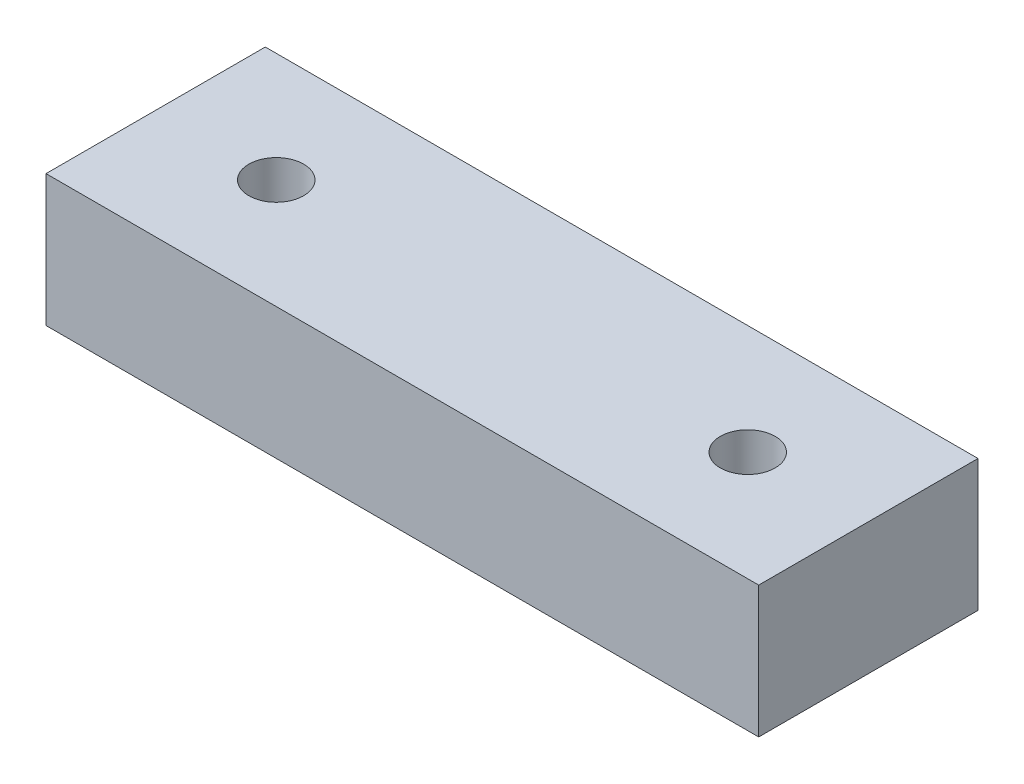
SolidWorks part; units mm, degrees
ref_plane "Front Plane" through (0, 0, 0) normal (0, 0, 1) x (1, 0, 0)
ref_plane "Top Plane" through (0, 0, 0) normal (0, 1, 0) x (1, 0, 0)
ref_plane "Right Plane" through (0, 0, 0) normal (1, 0, 0) x (0, 0, -1)
sketch "Sketch1" plane through (0, 0, 0) normal (0, 1, 0) x (1, 0, 0)
  line L1 (-32.5, -10) -> (32.5, -10)
  line L2 (-32.5, -10) -> (-32.5, 10)
  line L3 (-32.5, 10) -> (32.5, 10)
  line L4 (32.5, -10) -> (32.5, 10)
  line L5 (-32.5, -10) -> (32.5, 10) construction
  line L6 (-32.5, 10) -> (32.5, -10) construction
  point P0 (0, 0)
  dimension "D1" = 20
  dimension "55" = 65
extrude "Boss-Extrude1" add sketch "Sketch1" along normal blind 12
sketch "Sketch3" plane through (0, 0, 0) normal (0, -1, 0) x (-1, 0, 0)
  line L0 (-6.6, 0) -> (6.6, 0) construction
  line L1 (32.5, 10) -> (32.5, -10) construction
  line L2 (-32.5, -10) -> (-32.5, 10) construction
  circle A0 centre (21.5, 0) radius 2.5
  circle A1 centre (-21.5, 0) radius 2.5
  dimension "D1" = 5
  dimension "D2" = 11
  dimension "D3" = 11
extrude "Cut-Extrude1" cut sketch "Sketch3" against normal through all both and the other way through all
